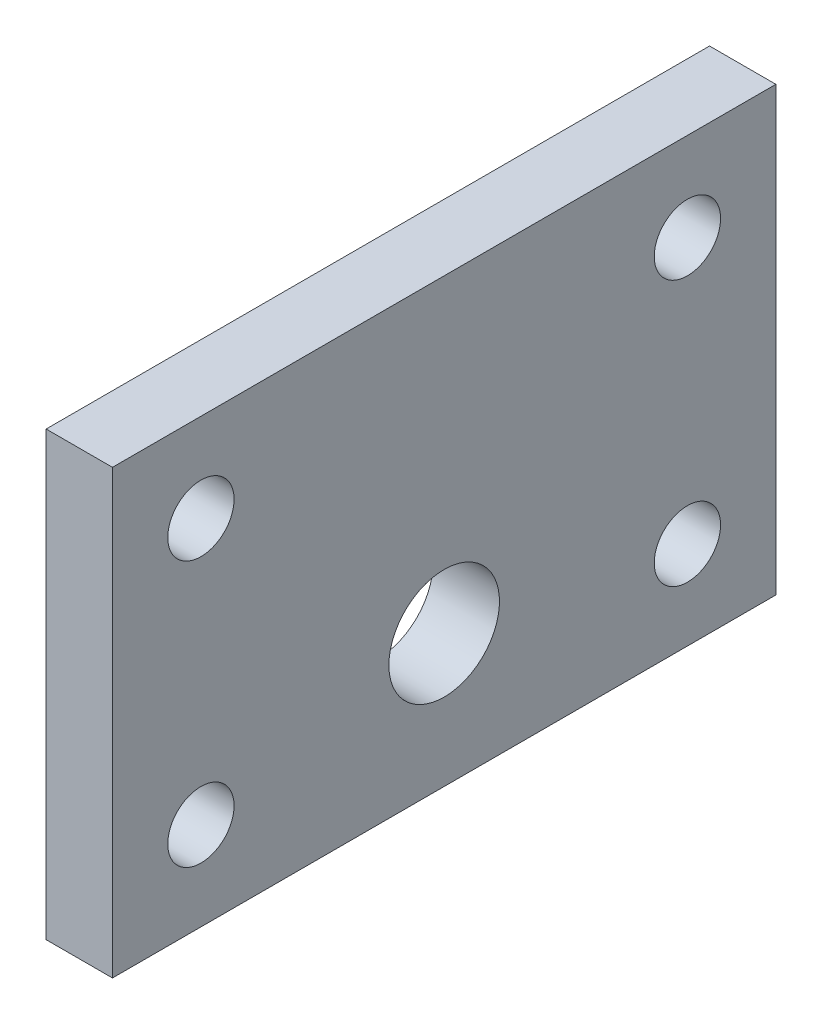
SolidWorks part; units mm, degrees
ref_plane "Front" through (0, 0, 0) normal (0, 0, 1) x (1, 0, 0)
ref_plane "Top" through (0, 0, 0) normal (0, 1, 0) x (1, 0, 0)
ref_plane "Right" through (0, 0, 0) normal (1, 0, 0) x (0, 0, -1)
sketch "草图1" plane through (0, 0, 0) normal (1, 0, 0) x (0, 0, -1)
  line L0 (-15, 0) -> (15, 0) construction
  line L1 (15, -10) -> (-15, -10)
  line L2 (15, -10) -> (15, 10)
  line L3 (15, 10) -> (-15, 10)
  line L4 (-15, -10) -> (-15, 10)
  line L5 (15, -10) -> (-15, 10) construction
  line L6 (15, 10) -> (-15, -10) construction
  circle A0 centre (0, 0) radius 3 construction
  circle A1 centre (-11, 6) radius 1.5
  circle A2 centre (-11, -6) radius 1.5
  circle A3 centre (11, -6) radius 1.5
  circle A4 centre (11, 6) radius 1.5
  point P0 (0, 0)
  point P16 (0, 0)
  point P19 (0, 0)
  point P20 (0, 0)
  point P21 (11, 6)
  point P22 (0, 0)
  dimension "D1" = 6
  dimension "D4" = 3
  dimension "D5" = 3
  dimension "D8" = 22
  dimension "D2" = 30
  dimension "D3" = 20
  dimension "D6" = 4
  dimension "D7" = 6
  dimension "D9" = 22
extrude "凸台-拉伸1" add sketch "草图1" along normal blind 3
sketch "草图2" plane through (0, 0, 0) normal (-1, 0, 0) x (0, 0, 1)
  line L0 (0, -10) -> (0, 10) construction
  line L1 (15, -10) -> (-15, -10) construction
  line L2 (-15, 10) -> (15, 10) construction
  circle A0 centre (0, -4) radius 2.5
  dimension "D1" = 5
  dimension "D2" = 14
extrude "切除-拉伸1" cut sketch "草图2" against normal up to next
